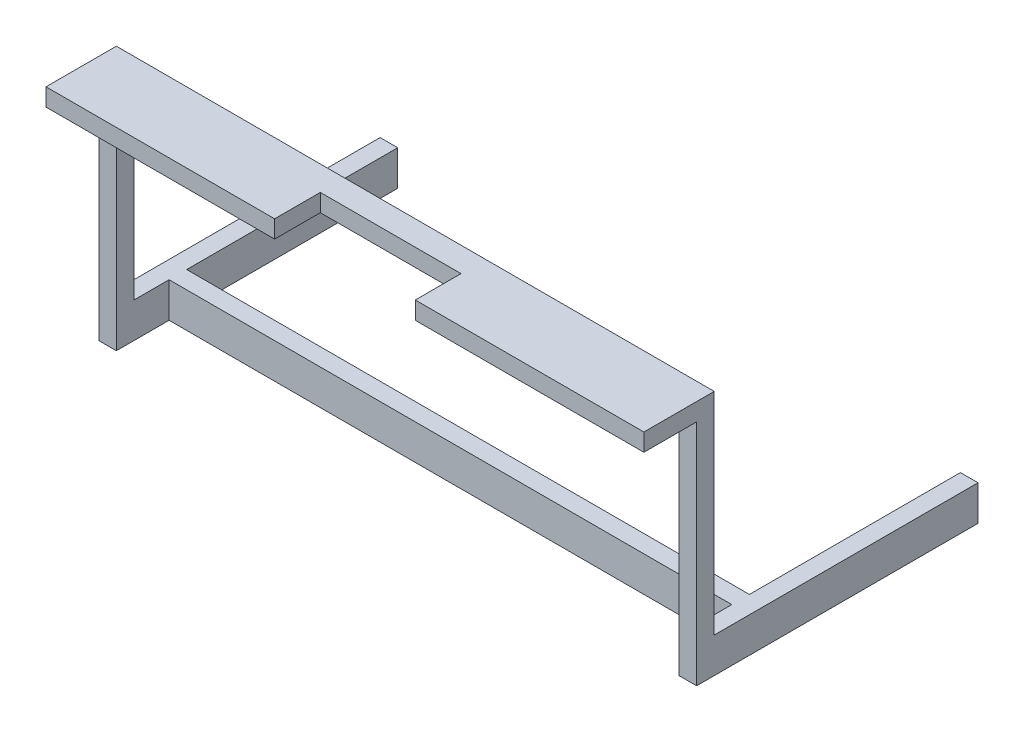
SolidWorks part; units mm, degrees
ref_plane "前视基准面" through (0, 0, 0) normal (0, 0, 1) x (1, 0, 0)
ref_plane "上视基准面" through (0, 0, 0) normal (0, 1, 0) x (1, 0, 0)
ref_plane "右视基准面" through (0, 0, 0) normal (1, 0, 0) x (0, 0, -1)
sketch "草图1" plane through (0, 0, 0) normal (1, 0, 0) x (0, 0, -1)
  line L0 (0, 0) -> (15, 0)
  line L1 (15, 0) -> (20, 0)
  line L2 (20, 0) -> (80, 0)
  line L3 (80, 0) -> (80, 10)
  line L4 (80, 10) -> (20, 10)
  line L5 (20, 10) -> (15, 10)
  line L8 (15, 10) -> (5, 10)
  line L9 (0, 0) -> (0, 65)
  line L10 (5, 10) -> (5, 70)
  line L11 (5, 70) -> (-15, 70)
  line L12 (0, 65) -> (-15, 65)
  line L13 (-15, 70) -> (-15, 65)
extrude "凸台-拉伸2" add sketch "草图1" along normal blind 170
sketch "草图5" plane through (0, 10, 0) normal (0, 1, 0) x (1, 0, 0)
  line L0 (5, 80) -> (165, 80)
  line L1 (170, 80) -> (0, 80) construction
  line L2 (5, 80) -> (5, 20)
  line L3 (5, 20) -> (165, 20)
  line L4 (165, 20) -> (165, 80)
extrude "切除-拉伸2" cut sketch "草图5" against normal blind 10
sketch "草图6" plane through (0, 10, 0) normal (0, 1, 0) x (1, 0, 0)
  line L0 (165, 15) -> (165, 5)
  line L1 (5, 15) -> (165, 15)
  line L2 (5, 15) -> (5, 5)
  line L3 (170, 5) -> (0, 5) construction
  line L4 (5, 5) -> (165, 5)
extrude "切除-拉伸3" cut sketch "草图6" against normal blind 10
sketch "草图7" plane through (0, 0, -5) normal (0, 0, -1) x (-1, 0, 0)
  line L0 (-165, 10) -> (-5, 10)
  line L1 (-5, 10) -> (-5, 65)
  line L2 (-5, 65) -> (-165, 65)
  line L3 (-165, 65) -> (-165, 10)
extrude "切除-拉伸4" cut sketch "草图7" against normal blind 5
sketch "草图8" plane through (0, 0, -5) normal (0, 0, -1) x (-1, 0, 0)
  line L0 (-165, 10) -> (-5, 10)
  line L1 (-5, 10) -> (-5, 0)
  line L2 (-5, 0) -> (-165, 0)
  line L3 (-165, 0) -> (-165, 10)
extrude "切除-拉伸5" cut sketch "草图8" against normal blind 5
sketch "草图9" plane through (0, 70, 0) normal (0, 1, 0) x (1, 0, 0)
  line L0 (85, -15) -> (105, -15)
  line L1 (170, -15) -> (0, -15) construction
  line L2 (65, -2) -> (105, -2)
  line L3 (105, -15) -> (105, -2)
  line L4 (85, -15) -> (65, -15)
  line L5 (65, -15) -> (65, -2)
extrude "切除-拉伸6" cut sketch "草图9" against normal blind 5
